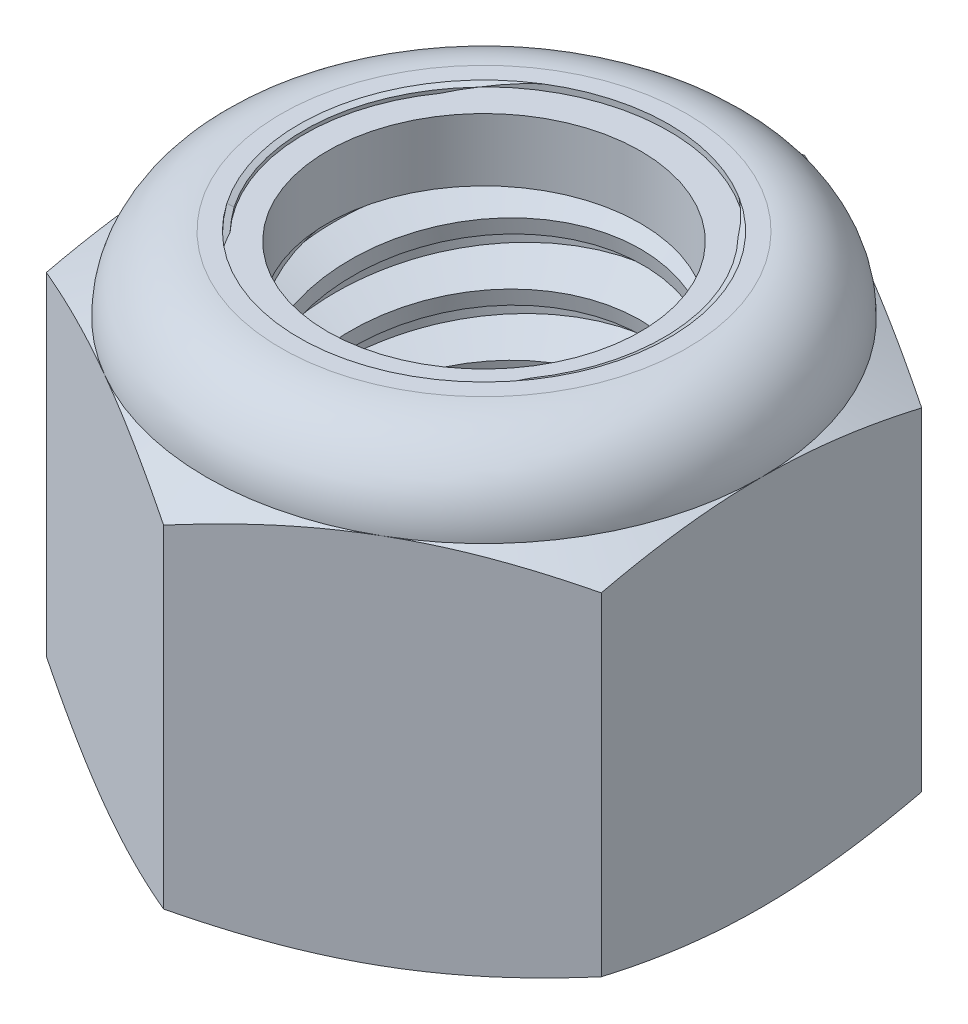
SolidWorks part; units mm, degrees
material "AISI 304"
ref_plane "Front" through (0, 0, 0) normal (0, 0, 1) x (1, 0, 0)
ref_plane "Top" through (0, 0, 0) normal (0, 1, 0) x (1, 0, 0)
ref_plane "Right" through (0, 0, 0) normal (1, 0, 0) x (0, 0, -1)
sketch "Sketch1" plane through (0, 0, 0) normal (0, 1, 0) x (1, 0, 0)
  line L1 (0, 8.2489) -> (-7.1437, 4.1244)
  line L2 (-7.1437, 4.1244) -> (-7.1437, -4.1244)
  line L3 (-7.1437, -4.1244) -> (0, -8.2489)
  line L4 (0, -8.2489) -> (7.1437, -4.1244)
  line L5 (7.1437, -4.1244) -> (7.1437, 4.1244)
  line L6 (7.1437, 4.1244) -> (0, 8.2489)
  circle A0 centre (0, 0) radius 7.1438 construction
  dimension "Hex Flats" = 14.2875
extrude "Extrude1" add sketch "Sketch1" along normal blind 11.5094
sketch "Sketch2" plane through (0, 0, 0) normal (1, 0, 0) x (0, 0, -1)
  line L0 (-4.7625, 0) -> (-4.7625, 11.5094) construction
  line L1 (0, 0) -> (4.7625, 0)
  line L2 (0, 0) -> (0, 11.5094)
  line L3 (0, 11.5094) -> (4.7625, 11.5094)
  line L4 (4.7625, 0) -> (4.7625, 11.5094)
  line L5 (-4.1244, 11.5094) -> (4.1244, 11.5094) construction
  line L7 (0, -4.7625) -> (0, 0) construction
  dimension "Thread Dia" = 9.525
revolve "Revolve1" add sketch "Sketch2" angle 360 about L7
sketch "Sketch3" plane through (0, 0, 0) normal (1, 0, 0) x (0, 0, -1)
  line L0 (4.7625, 11.5094) -> (-4.7625, 11.5094) construction
  line L1 (-4.7625, 11.5094) -> (-4.7625, 9.9219) construction
  line L2 (-4.7625, 9.9219) -> (4.7625, 11.5094) construction
  line L3 (4.7625, 11.5094) -> (4.7951, 11.3136) construction
  line L4 (4.7951, 11.3136) -> (5.0235, 9.9435)
  line L5 (5.0235, 9.9435) -> (4.0944, 10.2916)
  line L6 (4.0944, 10.2916) -> (4.0291, 10.683)
  line L7 (4.0291, 10.683) -> (4.7951, 11.3136)
  line L8 (4.0617, 10.4873) -> (4.9093, 10.6286) construction
  line L9 (4.7625, 11.5094) -> (4.7625, 10.6041) construction
  line L10 (4.7625, 10.6041) -> (-4.7625, 9.0166) construction
  line L11 (-4.7625, 9.0166) -> (-4.7625, 9.9219) construction
  line L12 (-0.2832, 11.5094) -> (0.2832, 8.1113) construction
  line L13 (-4.7625, 0) -> (-4.7625, 11.5094) construction
  line L14 (0, 11.5094) -> (4.7625, 11.5094) construction
  line L15 (4.7625, 0) -> (4.7625, 11.5094) construction
  point P13 (0, 9.8103)
  dimension "D1" = 0.1984
  dimension "D2" = 0.3969
  dimension "Thread Pitch" = 1.5875
  dimension "D4" = 60
  dimension "D5" = 1.5875
revolve "Cut-Revolve1" cut sketch "Sketch3" angle 360 about L12
pattern_linear "LPattern1" count 7 spacing 1.5875 along (0, -1, 0) count 2 spacing 1.5875 along (0, 1, 0) of "Cut-Revolve1"
sketch "Sketch4" plane through (0, 0, 0) normal (1, 0, 0) x (0, 0, -1)
  line L0 (0, 11.5094) -> (4.7625, 11.5094)
  line L1 (4.7625, 11.5094) -> (4.0291, 11.1674)
  line L2 (4.0291, 11.1674) -> (4.0291, 0.342)
  line L3 (4.0291, 0.342) -> (4.7625, 0)
  line L4 (4.7625, 0) -> (0, 0)
  line L5 (0, 0) -> (0, 11.5094)
  line L6 (4.7625, 0) -> (4.7625, 11.5094) construction
  line L7 (0, 11.5094) -> (4.7625, 11.5094) construction
  line L8 (0, 0) -> (4.7625, 0) construction
  line L9 (0, 0) -> (0, 11.5094) construction
  line L10 (0, 11.5094) -> (0, 12.3186) construction
  dimension "D1" = 25
revolve "Cut-Revolve2" cut sketch "Sketch4" angle 360 about L10
combine bodies "Combine1" operation type subtract main body 112 bodies to subtract 111
sketch "Sketch5" plane through (0, 0, 0) normal (1, 0, 0) x (0, 0, -1)
  line L0 (0, 0) -> (7.1438, 0)
  line L1 (7.1438, 0) -> (8.2489, 0.5153)
  line L2 (8.2489, 0.5153) -> (8.2489, 9.0758)
  line L3 (8.2489, 9.0758) -> (7.1437, 9.5911)
  line L4 (5.2255, 11.5094) -> (5.2255, 12.7794)
  line L5 (5.2255, 12.7794) -> (9.5189, 12.7794)
  line L6 (9.5189, 12.7794) -> (9.5189, -1.27)
  line L7 (9.5189, -1.27) -> (0, -1.27)
  line L8 (0, -1.27) -> (0, 0)
  line L9 (7.1437, 9.5911) -> (7.1438, 0) construction
  line L10 (0, 0) -> (4.7625, 0) construction
  line L13 (8.2489, 4.7956) -> (9.5189, 4.7956) construction
  line L14 (8.2489, 11.5094) -> (8.2489, 0) construction
  line L15 (0, 0) -> (0, 12.7794) construction
  line L20 (0, 12.7794) -> (5.2255, 12.7794) construction
  line L22 (0, 11.5094) -> (4.7625, 11.5094) construction
  arc A0 (7.1437, 9.5911) -> (5.2255, 11.5094) centre (5.2255, 9.5911) ccw
  dimension "D1" = 25
  dimension "D2" = 1.27
  dimension "D3" = 11.5094
  dimension "D4" = 1.9182
revolve "Cut-Revolve3" cut sketch "Sketch5" angle 360 about L15
sketch "Sketch6" plane through (0, 0, 0) normal (1, 0, 0) x (0, 0, -1)
  line L0 (0, 9.5911) -> (6.9914, 9.5911)
  line L1 (5.2255, 11.357) -> (4.6273, 11.357)
  line L2 (0, 12.7794) -> (0, 9.5911)
  line L3 (4.6273, 12.7794) -> (0, 12.7794)
  line L4 (0, 12.7794) -> (5.2255, 12.7794) construction
  line L5 (0, 0) -> (0, 12.7794) construction
  line L6 (0, 12.7794) -> (0, 44.323) construction
  line L7 (4.6273, 11.357) -> (4.6273, 12.7794)
  line L8 (5.2255, 11.5094) -> (5.2255, 11.357) construction
  line L9 (4.6273, 11.357) -> (4.0291, 11.357) construction
  line L10 (4.0291, 11.357) -> (4.0291, 11.1674) construction
  arc A0 (6.9914, 9.5911) -> (5.2255, 11.357) centre (5.2255, 9.5911) ccw
  arc A1 (7.1437, 9.5911) -> (5.2255, 11.5094) centre (5.2255, 9.5911) ccw construction
  dimension "D1" = 0.1524
revolve "Cut-Revolve4" cut sketch "Sketch6" angle 360 about L6
sketch "Sketch7" plane through (0, 0, 0) normal (1, 0, 0) x (0, 0, -1)
  line L0 (4.0291, 9.6673) -> (6.9134, 9.6673)
  line L1 (5.2255, 11.2808) -> (4.0291, 11.2808)
  line L2 (4.0291, 11.2808) -> (4.0291, 9.6673)
  line L3 (4.0291, 9.6673) -> (0, 9.6673) construction
  line L4 (0, 9.6673) -> (0, 11.2808) construction
  line L5 (0, 11.2808) -> (4.0291, 11.2808) construction
  line L6 (4.0291, 9.6673) -> (4.0291, 9.5911) construction
  line L7 (0, 9.5911) -> (6.9914, 9.5911) construction
  line L8 (5.2255, 11.2808) -> (5.2255, 11.357) construction
  arc A0 (6.9134, 9.6673) -> (5.2255, 11.2808) centre (5.2255, 9.5911) ccw
  arc A2 (6.9914, 9.5911) -> (5.2255, 11.357) centre (5.2255, 9.5911) ccw construction
  dimension "D1" = 0.0762
revolve "Revolve2" add sketch "Sketch7" angle 360 about L4
equation "\"D1@Sketch3\"=\"Thread Pitch@Sketch3\"/8"
equation "\"D2@Sketch3\"=\"Thread Pitch@Sketch3\"/4"
equation "\"D5@Sketch3\"=\"Thread Pitch@Sketch3\""
equation "\"D4@LPattern1\"=\"Thread Pitch@Sketch3\""
equation "\"D3@LPattern1\"=\"Thread Pitch@Sketch3\""
equation "\"D1@LPattern1\"=\"Height@Extrude1\"/\"Thread Pitch@Sketch3\""
equation "\"D4@Sketch5\"=\"Height@Extrude1\"/6"
